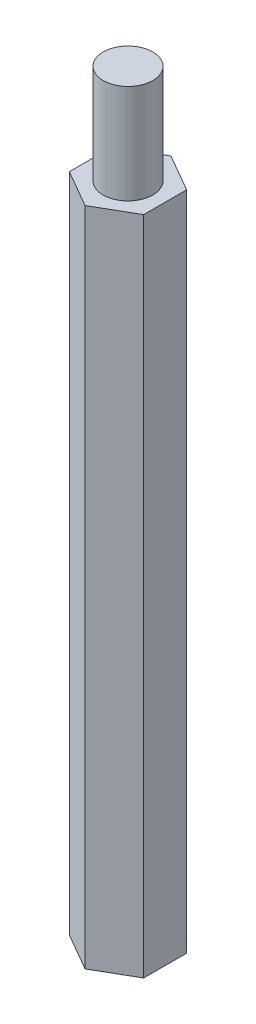
SolidWorks part; units mm, degrees
ref_plane "Front Plane" through (0, 0, 0) normal (0, 0, 1) x (1, 0, 0)
ref_plane "Top Plane" through (0, 0, 0) normal (0, 1, 0) x (1, 0, 0)
ref_plane "Right Plane" through (0, 0, 0) normal (1, 0, 0) x (0, 0, -1)
sketch "Sketch1" plane through (0, 0, 0) normal (0, 1, 0) x (1, 0, 0)
  line L1 (0, 2.5981) -> (-2.25, 1.299)
  line L2 (-2.25, 1.299) -> (-2.25, -1.299)
  line L3 (-2.25, -1.299) -> (0, -2.5981)
  line L4 (0, -2.5981) -> (2.25, -1.299)
  line L5 (2.25, -1.299) -> (2.25, 1.299)
  line L6 (2.25, 1.299) -> (0, 2.5981)
  circle A0 centre (0, 0) radius 2.25 construction
  dimension "D1" = 4.5
extrude "Boss-Extrude1" add sketch "Sketch1" along normal blind 40
sketch "Sketch2" plane through (0, 40, 0) normal (0, 1, 0) x (1, 0, 0)
  circle A0 centre (0, 0) radius 1.5
  dimension "D1" = 3
extrude "Cut-Extrude1" cut sketch "Sketch2" against normal blind 40
sketch "Sketch3" plane through (0, 40, 0) normal (0, 1, 0) x (1, 0, 0)
  circle A0 centre (0, 0) radius 1.5
extrude "Boss-Extrude2" add sketch "Sketch3" along normal blind 6 separate body
